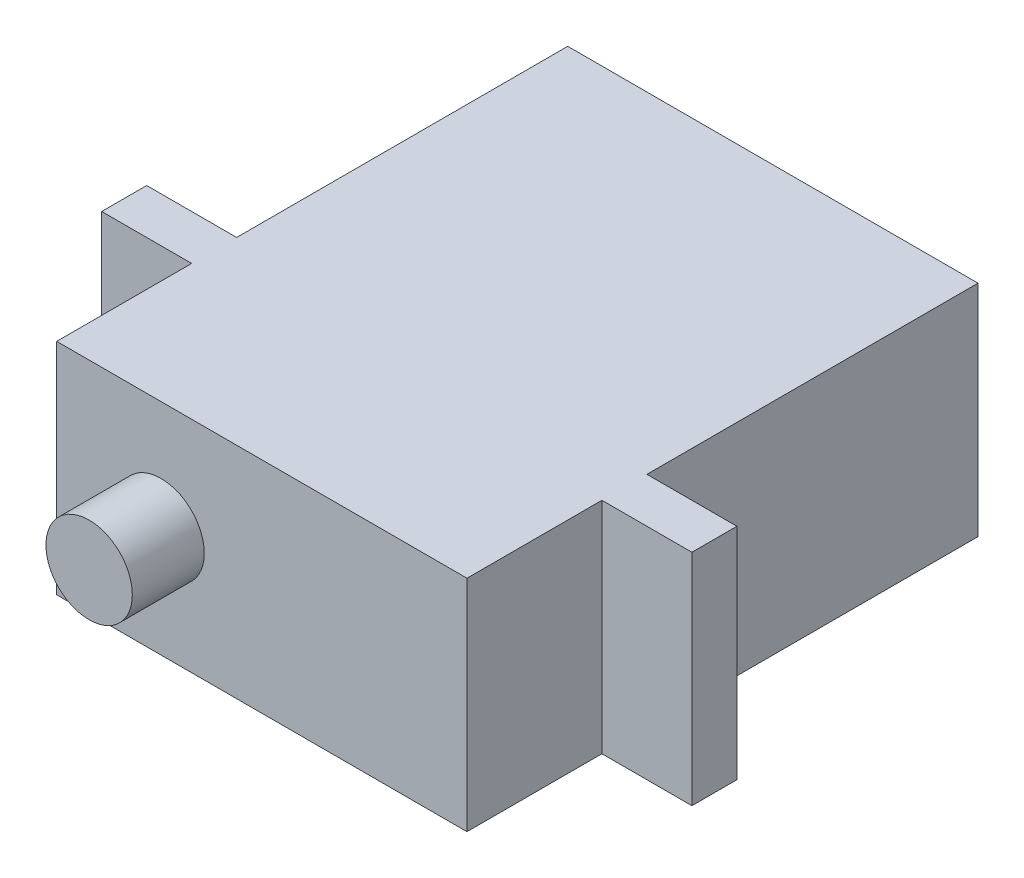
SolidWorks part; units mm, degrees
ref_plane "Front Plane" through (0, 0, 0) normal (0, 0, 1) x (1, 0, 0)
ref_plane "Top Plane" through (0, 0, 0) normal (0, 1, 0) x (1, 0, 0)
ref_plane "Right Plane" through (0, 0, 0) normal (1, 0, 0) x (0, 0, -1)
ref_plane "PZ_m32_400" through (0, 0, -32.4) normal (0, 0, 1) x (1, 0, 0)
sketch "S_box1" plane through (0, 0, -32.4) normal (0, 0, 1) x (1, 0, 0)
  line L0 (-5.8, -6.1) -> (17, -6.1)
  line L1 (17, -6.1) -> (17, 6.1)
  line L2 (17, 6.1) -> (-5.8, 6.1)
  line L3 (-5.8, 6.1) -> (-5.8, -6.1)
  dimension "P1" = 5.8
  dimension "P2" = 6.1
  dimension "P3" = 17
  dimension "P4" = 6.1
  dimension "P5" = 17
  dimension "P6" = 6.1
  dimension "P7" = 5.8
  dimension "P8" = 6.1
extrude "Boss_1" add sketch "S_box1" along normal blind 28.4
ref_plane "PZ_m14_000" through (0, 0, -14) normal (0, 0, 1) x (1, 0, 0)
sketch "S_box2" plane through (0, 0, -14) normal (0, 0, 1) x (1, 0, 0)
  line L0 (-10.8, -6.1) -> (22, -6.1)
  line L1 (22, -6.1) -> (22, 6.1)
  line L2 (22, 6.1) -> (-10.8, 6.1)
  line L3 (-10.8, 6.1) -> (-10.8, -6.1)
  dimension "P1" = 10.8
  dimension "P2" = 6.1
  dimension "P3" = 22
  dimension "P4" = 6.1
  dimension "P5" = 22
  dimension "P6" = 6.1
  dimension "P7" = 10.8
  dimension "P8" = 6.1
extrude "Boss_2" add sketch "S_box2" along normal blind 2.5
ref_plane "PZ_m4_500" through (0, 0, -4.5) normal (0, 0, 1) x (1, 0, 0)
sketch "S_cyl3" plane through (0, 0, -4.5) normal (0, 0, 1) x (1, 0, 0)
  circle A0 centre (0, 0) radius 2.4
  dimension "D1_S_cyl3" = 4.8
extrude "Boss_3" add sketch "S_cyl3" along normal blind 4.5
equation "\"plate_t\" = 3"
equation "\"clearance\" = 0.4"
